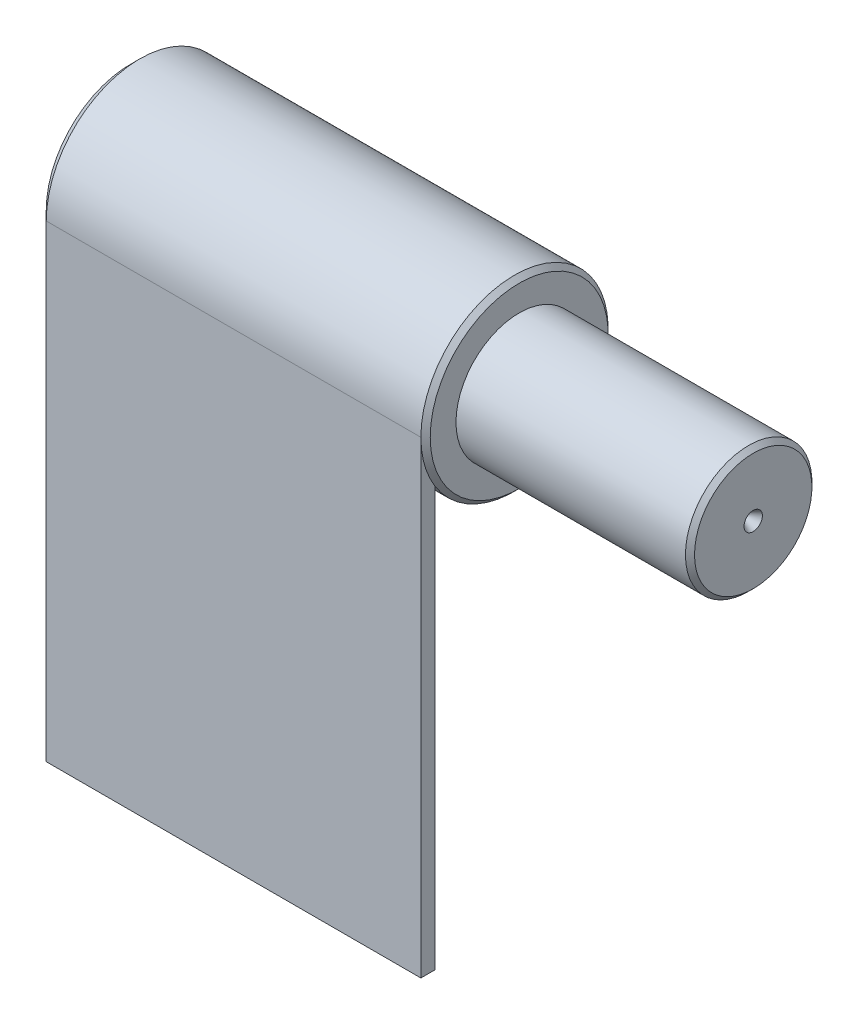
SolidWorks part; units mm, degrees
ref_plane "Спереди" through (0, 0, 0) normal (0, 0, 1) x (1, 0, 0)
ref_plane "Сверху" through (0, 0, 0) normal (0, 1, 0) x (1, 0, 0)
ref_plane "Справа" through (0, 0, 0) normal (1, 0, 0) x (0, 0, -1)
sketch "Эскиз2" plane through (0, 0, 0) normal (0, 1, 0) x (1, 0, 0)
  line L0 (-45.5275, 22.3375) -> (34.4725, 22.3375)
  line L1 (35.4725, 21.3375) -> (35.4725, 15.8375)
  line L2 (35.4725, 15.8375) -> (84.4725, 15.8375)
  line L3 (-47.5275, 20.3375) -> (-47.5275, 2.3375)
  line L4 (85.4416, 14.8685) -> (85.4416, 4.2964)
  line L5 (-47.5275, 2.3375) -> (82.2592, 2.3375)
  line L6 (34.4725, 22.3375) -> (35.4725, 21.3375)
  line L7 (-58.608, 2.3375) -> (159.8552, 2.3375) construction
  line L8 (84.4725, 15.8375) -> (85.4416, 14.8685)
  line L9 (-45.5275, 22.3375) -> (-47.5275, 20.3375)
  line L10 (82.2592, 2.3375) -> (85.4416, 4.2964)
  point P1 (35.4725, 22.3375)
  point P4 (85.4725, 15.8375)
  point P10 (-47.5275, 22.3375)
  dimension "D1" = 20
  dimension "D2" = 13.5
  dimension "D3" = 2
  dimension "D4" = 45
revolve "Повернуть1" add sketch "Эскиз2" angle 360 about L7
sketch "Эскиз3" plane through (0, 0, 0) normal (0, 1, 0) x (1, 0, 0)
  line L0 (34.4725, -17.6625) -> (34.4725, 22.3375) construction
  line L1 (-45.5275, -17.6625) -> (34.4725, -17.6625)
  line L2 (-45.5275, -17.6625) -> (-45.5275, -14.6624)
  line L3 (-45.5275, -14.6624) -> (34.4725, -14.6624)
  line L4 (34.4725, -17.6625) -> (34.4725, -14.6624)
extrude "Бобышка-Вытянуть1" add sketch "Эскиз3" against normal blind 100
